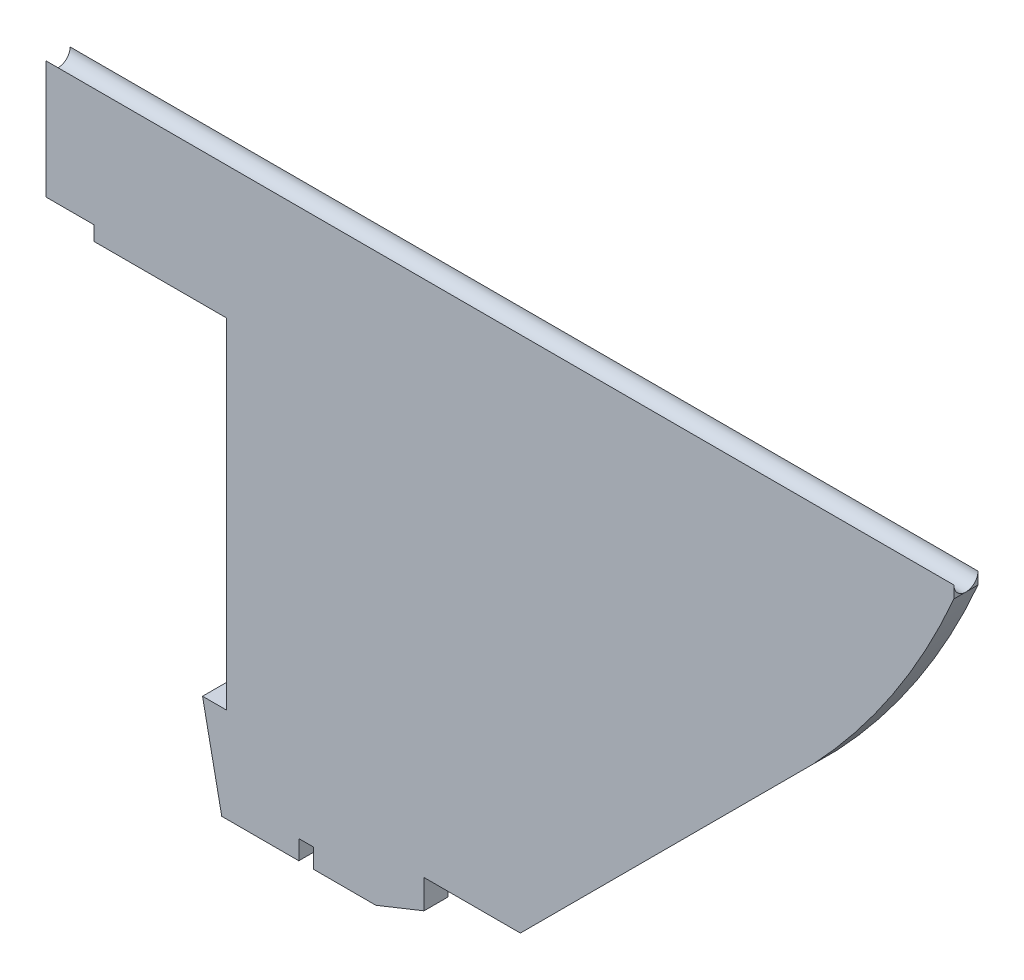
SolidWorks part; units mm, degrees
material "Papier ondulé"
ref_plane "Plan de face" through (0, 0, 0) normal (0, 0, 1) x (1, 0, 0)
ref_plane "Plan de dessus" through (0, 0, 0) normal (0, 1, 0) x (1, 0, 0)
ref_plane "Plan de droite" through (0, 0, 0) normal (1, 0, 0) x (0, 0, -1)
sketch "Esquisse1" plane through (0, 0, 0) normal (0, 0, 1) x (1, 0, 0)
  line L0 (0, 0) -> (188.5, 0) construction
  line L1 (0, 0) -> (0, -25)
  line L2 (0, -25) -> (37.5, -25)
  line L3 (37.5, -25) -> (37.5, -95.5)
  line L4 (37.5, -95.5) -> (32.5, -95.5)
  line L5 (32.5, -95.5) -> (36.4874, -115.0985)
  line L6 (36.4874, -115.0985) -> (88.4874, -115.0985)
  line L7 (88.4874, -115.0985) -> (159.198, -44.3878)
  line L8 (43.6829, 43.9989) -> (200.1829, 45.1267)
  arc A0 (0, 0) -> (43.6829, 43.9989) centre (44, 0) cw
  arc A1 (159.198, -44.3878) -> (200.1829, 45.1267) centre (49.0805, 60.1702) ccw
extrude "Boss.-Extru.1" add sketch "Esquisse1" along normal blind 5
sketch "Esquisse2" plane through (0, 0, 5) normal (0, 0, 1) x (1, 0, 0)
  line L0 (0, 0) -> (188.5, 0)
  line L2 (0, 0) -> (-15.6326, 12.4435)
  line L3 (-15.6326, 12.4435) -> (19.4776, 66.0889)
  line L4 (19.4776, 66.0889) -> (219.452, 63.38)
  line L5 (219.452, 63.38) -> (209.3622, -2.4607)
  line L6 (209.3622, -2.4607) -> (188.5, 0)
sketch "Esquisse3" plane through (0, 0, 5) normal (0, 0, 1) x (1, 0, 0)
  line L1 (0, -25) -> (10, -25)
  line L2 (0, -25) -> (0, -22)
  line L3 (0, -22) -> (10, -22)
  line L4 (10, -25) -> (10, -22)
extrude "Enlèv. mat.-Extru.1" cut sketch "Esquisse3" against normal through all
sketch "Esquisse4" plane through (0, 0, 5) normal (0, 0, 1) x (1, 0, 0)
  line L0 (88.4874, -115.0985) -> (88.4874, -105.0985) construction
  line L1 (88.4874, -105.0985) -> (78.4874, -105.0985)
  line L2 (78.4874, -105.0985) -> (78.4874, -115.0985) construction
  line L3 (36.4874, -115.0985) -> (88.4874, -115.0985) construction
  line L4 (78.4874, -115.0985) -> (88.4874, -115.0985)
  line L5 (88.4874, -105.0985) -> (98.4874, -105.0985)
  line L6 (88.4874, -115.0985) -> (159.198, -44.3878) construction
  line L7 (98.4874, -105.0985) -> (88.4874, -115.0985)
  line L8 (78.4874, -105.0985) -> (78.4874, -111.0985)
  line L9 (78.4874, -111.0985) -> (68.4874, -115.0985)
  line L10 (68.4874, -115.0985) -> (78.4874, -115.0985)
extrude "Enlèv. mat.-Extru.2" cut sketch "Esquisse4" against normal through all
extrude "Enlèv. mat.-Extru.3" cut sketch "Esquisse2" against normal through all
sketch "Esquisse5" plane through (0, 0, 0) normal (-1, 0, 0) x (0, 0, 1)
  line L0 (5, 0) -> (5, 2.5)
  line L1 (5, 0) -> (2.5, 0)
  line L2 (5, 0) -> (0, 0) construction
  line L3 (2.5, 0) -> (0, 0)
  line L4 (0, 0) -> (0, 2.5)
  arc A0 (0, 2.5) -> (5, 2.5) centre (2.5, 2.5) ccw
extrude "Boss.-Extru.2" add sketch "Esquisse5" along direction (1, 0, 0) on the side against the normal up to vertex (188.5 mm away)
sketch "Esquisse6" plane through (0, 0, 0) normal (0, 0, -1) x (-1, 0, 0)
  line L0 (-78.4874, -111.0985) -> (-55.4874, -111.0985) construction
  line L1 (-36.4874, -115.0985) -> (-68.4874, -115.0985) construction
  line L2 (-55.4874, -111.0985) -> (-52.4874, -111.0985)
  line L3 (-55.4874, -111.0985) -> (-55.4874, -115.0985)
  line L4 (-55.4874, -115.0985) -> (-52.4874, -115.0985)
  line L5 (-52.4874, -111.0985) -> (-52.4874, -115.0985)
  dimension "D1" = 23
  dimension "D2" = 3
extrude "Enlèv. mat.-Extru.4" cut sketch "Esquisse6" against normal through all
